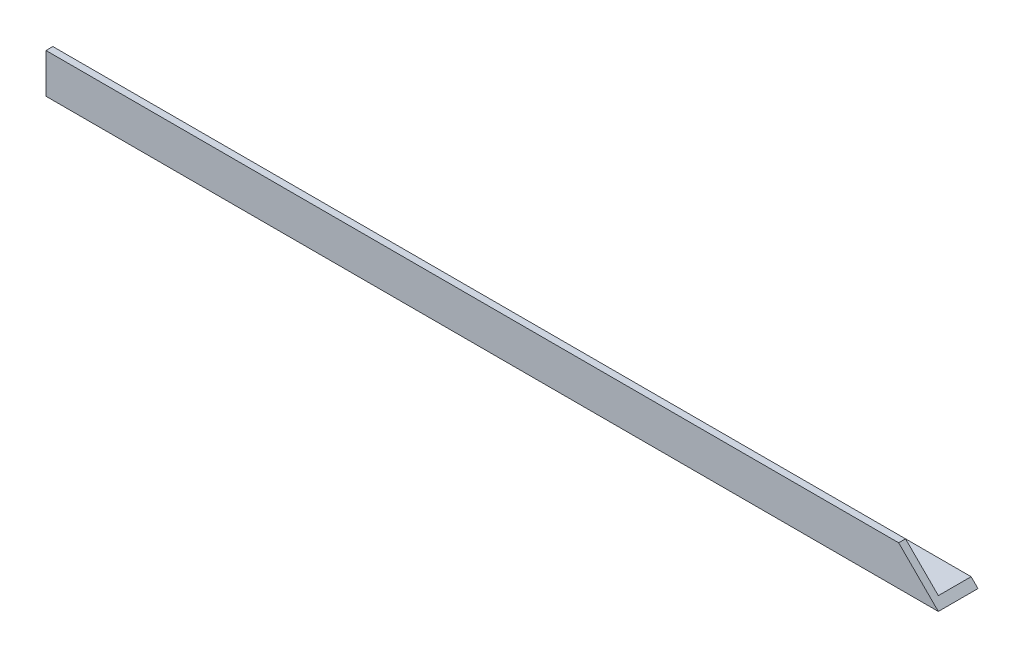
SolidWorks part; units mm, degrees
ref_plane "Front Plane" through (0, 0, 0) normal (0, 0, 1) x (1, 0, 0)
ref_plane "Top Plane" through (0, 0, 0) normal (0, 1, 0) x (1, 0, 0)
ref_plane "Right Plane" through (0, 0, 0) normal (1, 0, 0) x (0, 0, -1)
sketch "Sketch1" plane through (0, 0, 0) normal (1, 0, 0) x (0, 0, -1)
  line L0 (0, 0) -> (20, 0)
  line L1 (20, 0) -> (20, 3.4612)
  line L2 (20, 3.4612) -> (3.4612, 3.4612)
  line L3 (3.4612, 3.4612) -> (3.4612, 20)
  line L4 (3.4612, 20) -> (0, 20)
  line L5 (0, 20) -> (0, 0)
  dimension "D1" = 3.4612
  dimension "D2" = 20
extrude "Boss-Extrude1" add sketch "Sketch1" along normal blind 450
sketch "Sketch2" plane through (0, 0, 0) normal (0, 0, -1) x (1, 0, 0)
  line L4 (450, 0) -> (430, -20)
  line L5 (450, -20) -> (0, -20) construction
  line L6 (430, -20) -> (450, -20)
  line L7 (450, -20) -> (450, 0)
extrude "Cut-Extrude1" cut sketch "Sketch2" along normal through all
